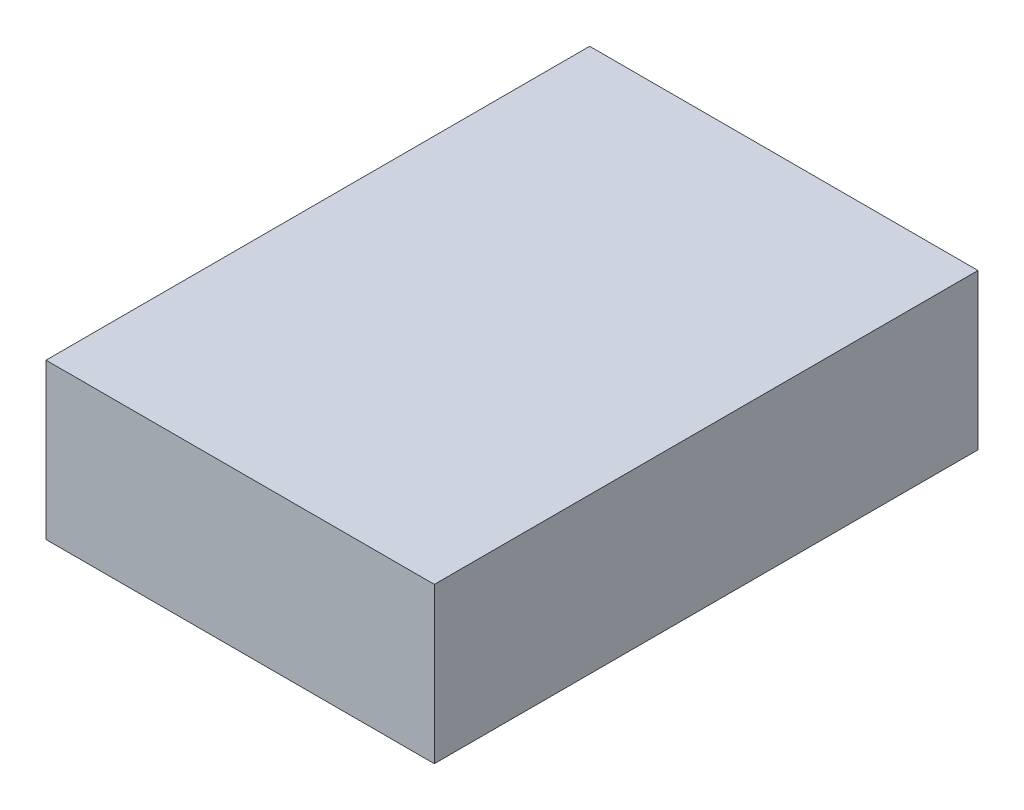
SolidWorks part; units mm, degrees
ref_plane "Ebene vorne" through (0, 0, 0) normal (0, 0, 1) x (1, 0, 0)
ref_plane "Ebene oben" through (0, 0, 0) normal (0, 1, 0) x (1, 0, 0)
ref_plane "Ebene rechts" through (0, 0, 0) normal (1, 0, 0) x (0, 0, -1)
sketch "Sketch1" plane through (0, 0, 0) normal (0, 0, 1) x (1, 0, 0)
  line L1 (-12.5, 5) -> (12.5, 5)
  line L2 (-12.5, 5) -> (-12.5, -5)
  line L3 (-12.5, -5) -> (12.5, -5)
  line L4 (12.5, 5) -> (12.5, -5)
  line L5 (0, -5) -> (0, 5) construction
  line L6 (-12.5, 0) -> (12.5, 0) construction
  point P0 (0, 0)
  dimension "D1" = 25
  dimension "D2" = 10
extrude "Boss-Extrude1" add sketch "Sketch1" along normal blind 35
equation "\"A\"= 25"
equation "\"B\"=     10"
equation "\"C\"=   \"A\" + \"B\""
equation "\"D1@Sketch1\" = \"A\""
equation "\"D2@Sketch1\"=\"B\""
equation "\"D1@Boss-Extrude1\"=\"C\""
